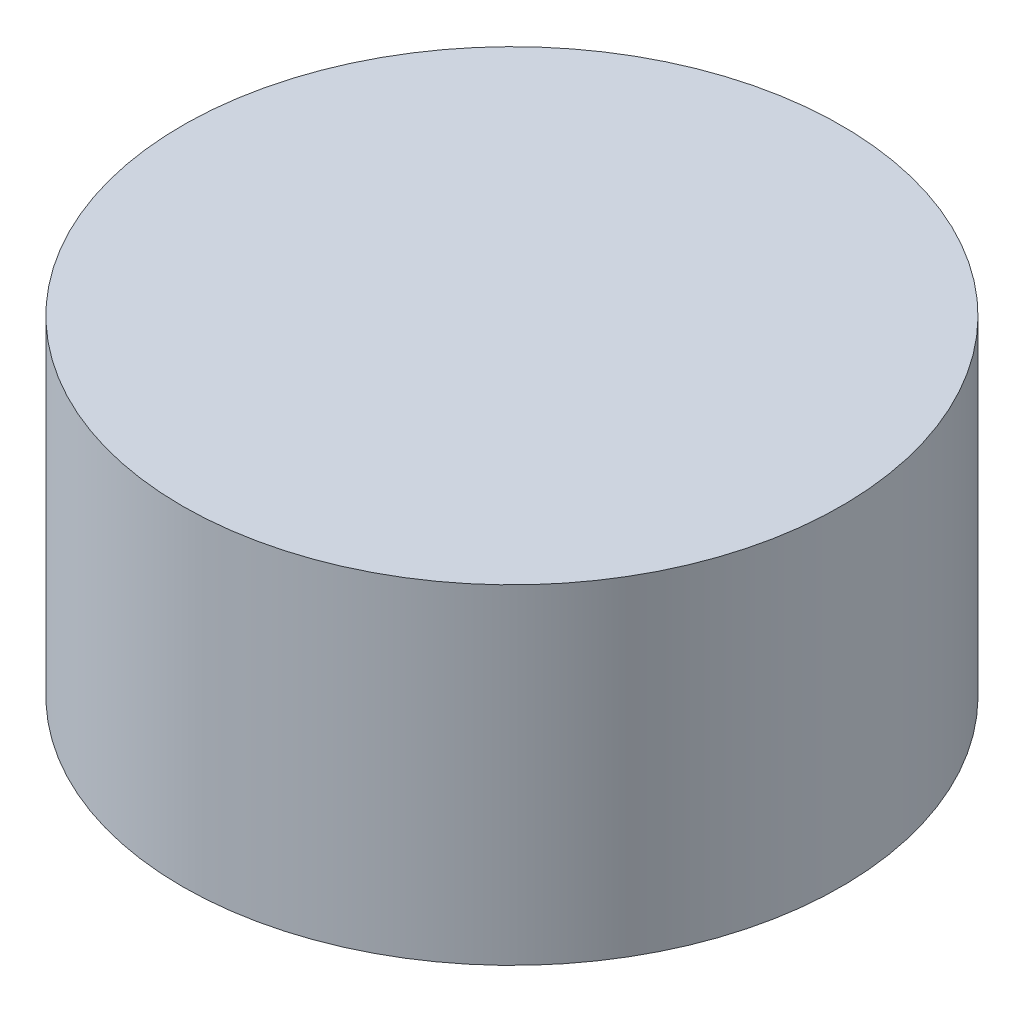
SolidWorks part; units mm, degrees
ref_plane "Front Plane" through (0, 0, 0) normal (0, 0, 1) x (1, 0, 0)
ref_plane "Top Plane" through (0, 0, 0) normal (0, 1, 0) x (1, 0, 0)
ref_plane "Right Plane" through (0, 0, 0) normal (1, 0, 0) x (0, 0, -1)
sketch "Sketch1" plane through (0, 0, 0) normal (0, 1, 0) x (1, 0, 0)
  circle A0 centre (0, 0) radius 2
  dimension "D1" = 4
extrude "Boss-Extrude1" add sketch "Sketch1" along normal blind 2
equation "\"a\"= 1"
equation "\"b\"= 1"
equation "\"c\"= 1"
equation "\"d\"= 1"
equation "\"e\"= 1"
equation "\"x\"= 1"
equation "\"y\"= 1"
equation "\"z\"= 1"
